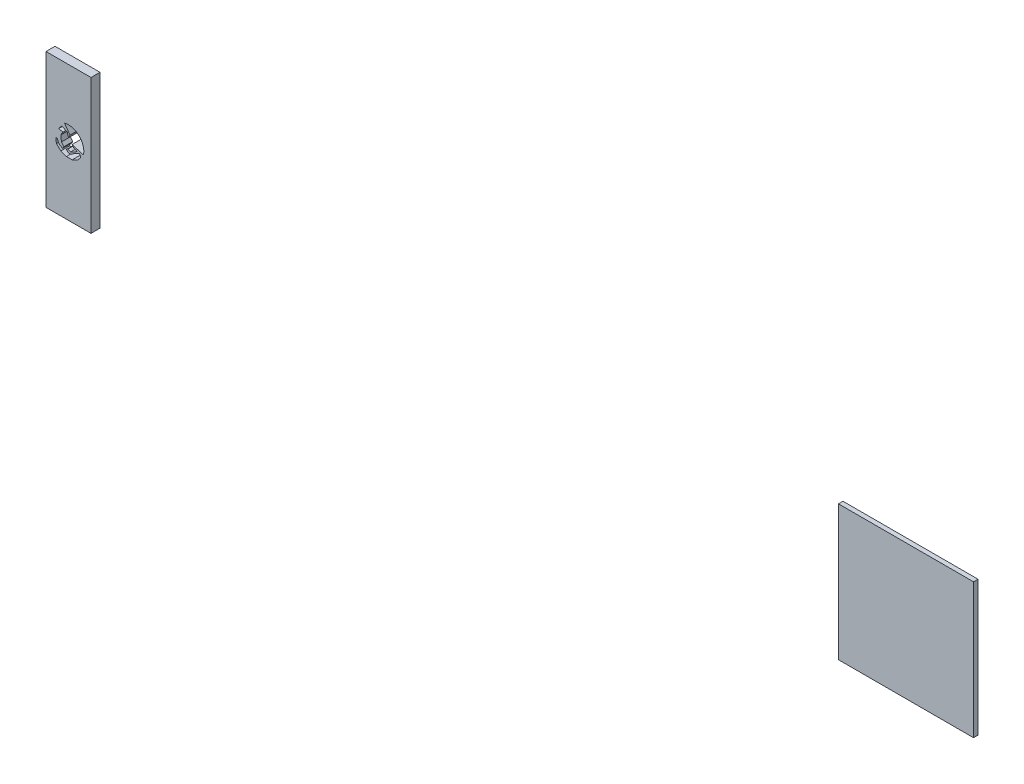
SolidWorks part; units mm, degrees
ref_plane "Alzado" through (0, 0, 0) normal (0, 0, 1) x (1, 0, 0)
ref_plane "Planta" through (0, 0, 0) normal (0, 1, 0) x (1, 0, 0)
ref_plane "Vista lateral" through (0, 0, 0) normal (1, 0, 0) x (0, 0, -1)
sketch "Croquis1" plane through (0, 0, 0) normal (0, 0, 1) x (1, 0, 0)
  line L1 (38.764, 25.3151) -> (53.764, 25.3151)
  line L2 (38.764, 25.3151) -> (38.764, 10.3151)
  line L3 (38.764, 10.3151) -> (53.764, 10.3151)
  line L4 (53.764, 25.3151) -> (53.764, 10.3151)
extrude "Saliente-Extruir1" add sketch "Croquis1" along normal blind 0.5
sketch "Croquis2" plane through (0, 0, 0) normal (0, 0, 1) x (1, 0, 0)
  line L0 (-53.764, 10.3151) -> (-38.764, 10.3151) construction
  line L1 (-48.764, 25.3151) -> (-43.764, 25.3151)
  line L2 (-48.764, 25.3151) -> (-48.764, 10.3151)
  line L3 (-48.764, 10.3151) -> (-43.764, 10.3151)
  line L4 (-43.764, 25.3151) -> (-43.764, 10.3151)
  line L6 (-53.764, 10.3151) -> (-48.764, 10.3151) construction
  line L9 (-46.264, 17.8151) -> (-46.264, 10.3151) construction
  line L10 (-46.264, 17.8151) -> (-48.764, 17.8151) construction
  line L11 (-46.7024, 19.4564) -> (-46.1047, 18.6003)
  line L12 (-46.1047, 18.6003) -> (-46.264, 18.2623)
  line L13 (-46.264, 18.2623) -> (-46.4035, 18.7411)
  line L14 (-46.4035, 18.7411) -> (-47.013, 19.0283)
  line L15 (-47.013, 19.0283) -> (-47.36, 18.6003)
  line L16 (-47.36, 18.6003) -> (-46.8888, 18.5017)
  line L17 (-46.8888, 18.5017) -> (-47.1244, 18.1014)
  line L18 (-47.1244, 18.1014) -> (-47.0517, 17.4656)
  line L19 (-47.0517, 17.4656) -> (-46.7768, 17.1448)
  line L20 (-46.7768, 17.1448) -> (-46.9143, 16.9113)
  line L21 (-46.9143, 16.9113) -> (-47.3111, 17.1448)
  line L22 (-47.3111, 17.1448) -> (-47.514, 17.563)
  line L23 (-47.514, 17.563) -> (-47.6866, 17.5991)
  line L24 (-47.6866, 17.5991) -> (-47.6003, 17.0281)
  line L25 (-47.6003, 17.0281) -> (-47.1127, 16.5742)
  line L26 (-47.1127, 16.5742) -> (-46.4893, 16.3447)
  line L27 (-46.4893, 16.3447) -> (-45.8567, 16.3447)
  line L28 (-45.8567, 16.3447) -> (-45.2549, 16.6367)
  line L29 (-45.2549, 16.6367) -> (-44.9302, 16.9856)
  line L30 (-44.9302, 16.9856) -> (-44.9302, 17.1991)
  line L31 (-44.9302, 17.1991) -> (-45.0926, 17.3503)
  line L32 (-45.0926, 17.3503) -> (-45.4733, 17.1655)
  line L33 (-45.4733, 17.1655) -> (-45.9809, 16.8112)
  line L34 (-45.9809, 16.8112) -> (-46.3338, 16.8112)
  line L35 (-46.3338, 16.8112) -> (-46.4893, 17.034)
  line L36 (-46.4893, 17.034) -> (-46.3338, 17.1426)
  line L37 (-46.3338, 17.1426) -> (-46.0229, 17.0282)
  line L38 (-46.0229, 17.0282) -> (-45.5558, 17.2548)
  line L39 (-45.5558, 17.2548) -> (-45.2829, 17.4453)
  line L40 (-45.2829, 17.4453) -> (-45.7271, 17.6088)
  line L41 (-45.7271, 17.6088) -> (-45.871, 17.8151)
  line L42 (-45.871, 17.8151) -> (-44.6058, 17.4453)
  arc A0 (-44.6058, 17.4453) -> (-46.7024, 19.4564) centre (-46.264, 17.8151) ccw
extrude "Saliente-Extruir2" add sketch "Croquis2" along normal blind 1 separate body
